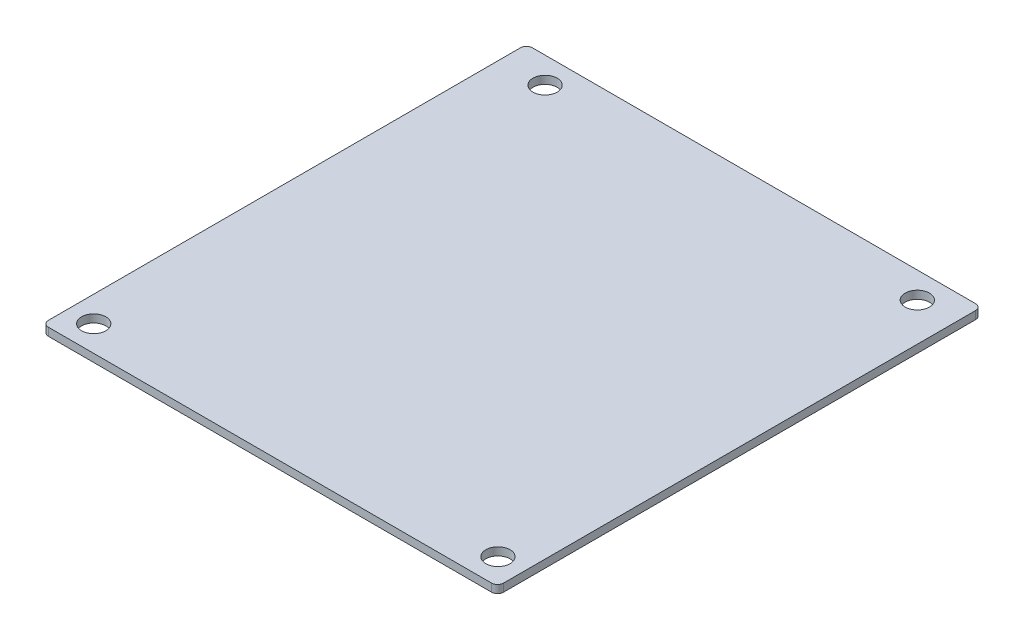
SolidWorks part; units mm, degrees
ref_plane "Front Plane" through (0, 0, 0) normal (0, 0, 1) x (1, 0, 0)
ref_plane "Top Plane" through (0, 0, 0) normal (0, 1, 0) x (1, 0, 0)
ref_plane "Right Plane" through (0, 0, 0) normal (1, 0, 0) x (0, 0, -1)
sketch "Sketch1" plane through (0, 0, 0) normal (0, 1, 0) x (1, 0, 0)
  line L1 (-45.085, -47.945) -> (45.085, -47.945)
  line L2 (-45.085, -47.945) -> (-45.085, 47.945)
  line L3 (-45.085, 47.945) -> (45.085, 47.945)
  line L4 (45.085, -47.945) -> (45.085, 47.945)
  line L5 (-45.085, -47.945) -> (45.085, 47.945) construction
  line L6 (-45.085, 47.945) -> (45.085, -47.945) construction
  point P0 (0, 0)
  dimension "D1" = 95.89
  dimension "D2" = 90.17
extrude "Boss-Extrude1" add sketch "Sketch1" along normal blind 1.57
sketch "Sketch3" plane through (0, 1.57, 0) normal (0, 1, 0) x (1, 0, 0)
  line L0 (-45.085, -47.945) -> (-40.005, -47.945) construction
  line L1 (-45.085, -47.945) -> (45.085, -47.945) construction
  line L2 (-40.005, -47.945) -> (-40.005, -42.865) construction
  line L3 (45.085, -47.945) -> (40.005, -47.945) construction
  line L4 (-45.085, -47.945) -> (45.085, -47.945) construction
  line L5 (40.005, -47.945) -> (40.005, -42.785) construction
  line L6 (-45.085, 47.945) -> (-36.235, 47.945) construction
  line L7 (45.085, 47.945) -> (-45.085, 47.945) construction
  line L8 (-36.235, 47.945) -> (-36.235, 42.785) construction
  line L9 (45.085, 47.945) -> (-45.085, 47.945) construction
  line L10 (-45.085, -47.945) -> (45.085, -47.945) construction
  line L11 (45.085, -47.945) -> (45.085, 47.945) construction
  line L12 (-45.085, 47.945) -> (-45.085, -47.945) construction
  circle A0 centre (-40.005, -42.865) radius 2.4
  circle A1 centre (40.005, -42.785) radius 2.4
  circle A2 centre (-36.235, 42.785) radius 2.4
  circle A3 centre (37.515, 42.785) radius 2.4
  dimension "D3" = 4.8
  dimension "D6" = 5.16
  dimension "D4" = 5.08
  dimension "D5" = 4.8
  dimension "D7" = 4.8
  dimension "D8" = 4.8
  dimension "D1" = 5.08
  dimension "D2" = 5.08
  dimension "D9" = 5.16
  dimension "D10" = 5.16
  dimension "D11" = 7.57
  dimension "7.85mm" = 8.85
extrude "Cut-Extrude2" cut sketch "Sketch3" against normal blind 1.57
fillet "Fillet10" radius 1.2 1 edges at (45.085, 0.785, 47.945)
fillet "Fillet11" radius 1.2 1 edges at (45.085, 0.785, -47.945)
fillet "Fillet14" radius 1.2 1 edges at (-45.085, 0.785, -47.945)
fillet "Fillet21" radius 1.2 1 edges at (-45.085, 0.785, 47.945)
